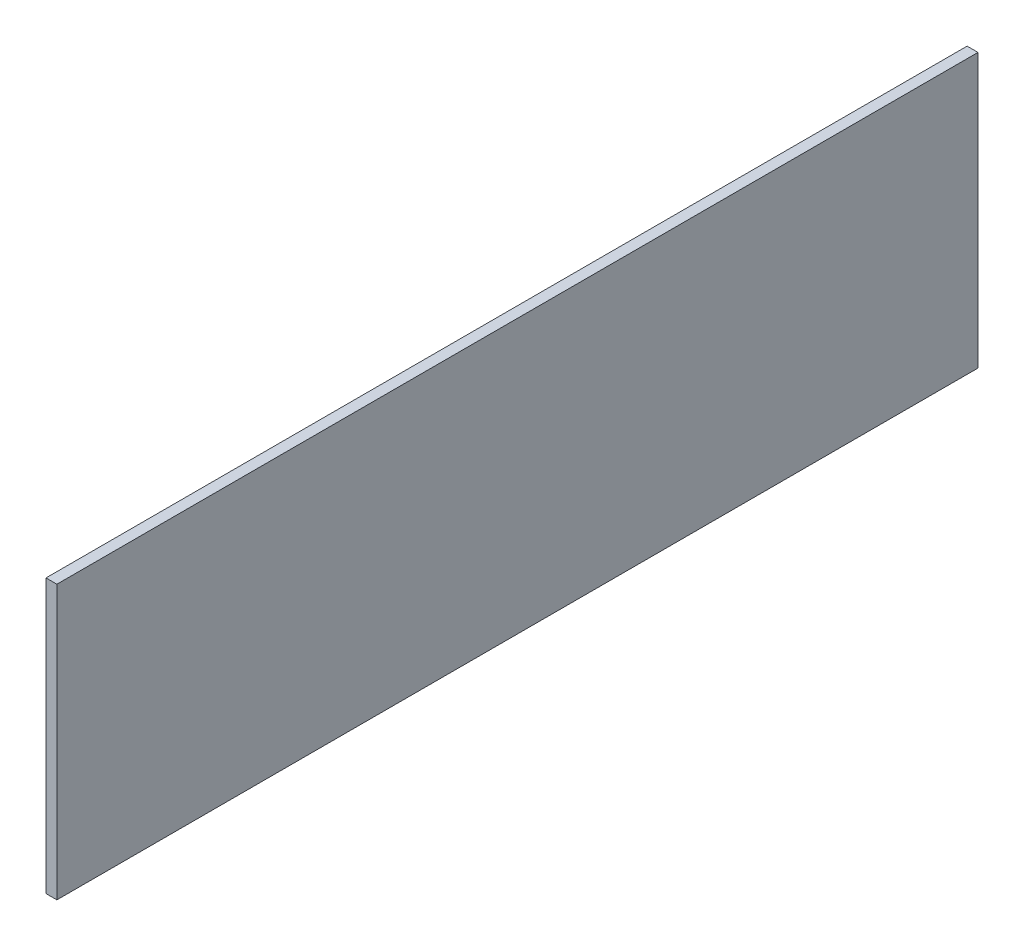
SolidWorks part; units mm, degrees
ref_plane "Alzado" through (0, 0, 0) normal (0, 0, 1) x (1, 0, 0)
ref_plane "Planta" through (0, 0, 0) normal (0, 1, 0) x (1, 0, 0)
ref_plane "Vista lateral" through (0, 0, 0) normal (1, 0, 0) x (0, 0, -1)
sketch "Croquis1" plane through (0, 0, 0) normal (0, 0, 1) x (1, 0, 0)
  line L8 (84.0143, -28.8051) -> (85.1143, -28.8051)
  line L9 (85.1143, -28.8051) -> (85.1143, -1.2022)
  line L10 (85.1143, -1.2022) -> (84.0143, -1.2022)
  line L11 (84.0143, -1.2022) -> (84.0143, -28.8051)
  line L12 (84.0143, -28.8051) -> (85.1143, -28.8051)
  line L13 (85.1143, -28.8051) -> (85.1143, -1.2022)
  line L14 (85.1143, -1.2022) -> (84.0143, -1.2022)
  line L15 (84.0143, -1.2022) -> (84.0143, -28.8051)
  dimension "D1" = 0.2
extrude "Saliente-Extruir1" add sketch "Croquis1" along normal blind 93
